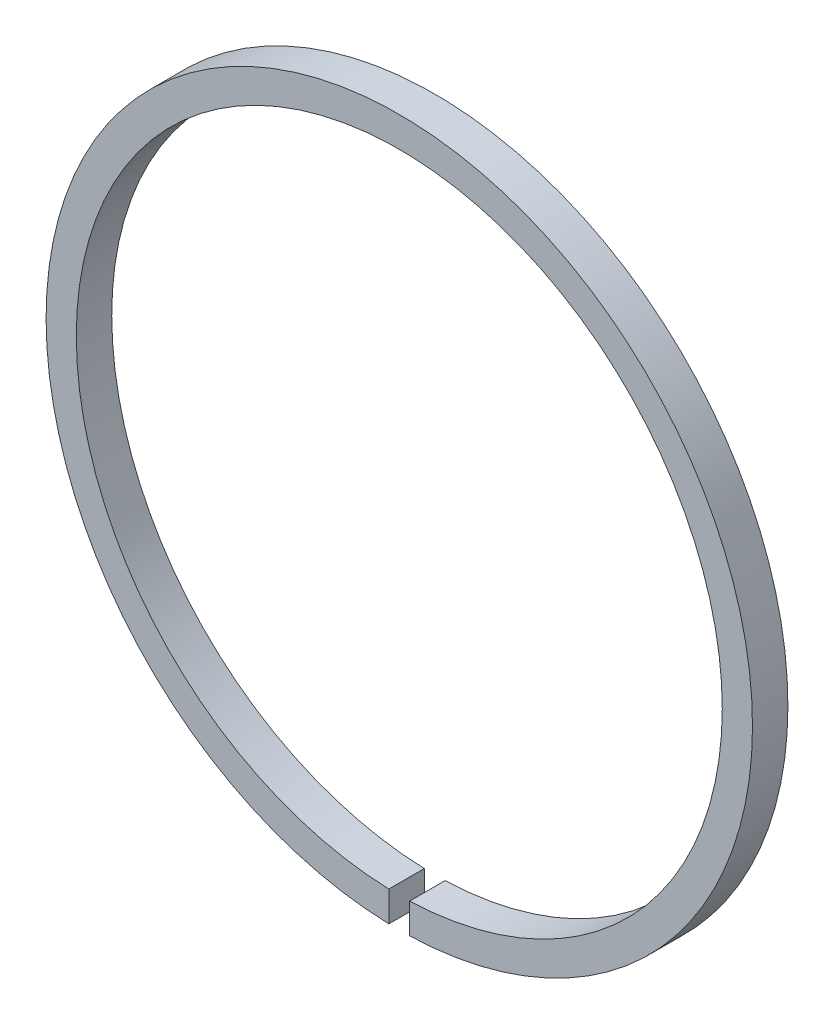
SolidWorks part; units mm, degrees
material "Copper"
ref_plane "Front Plane" through (0, 0, 0) normal (0, 0, 1) x (1, 0, 0)
ref_plane "Top Plane" through (0, 0, 0) normal (0, 1, 0) x (1, 0, 0)
ref_plane "Right Plane" through (0, 0, 0) normal (1, 0, 0) x (0, 0, -1)
sketch "Sketch1" plane through (0, 0, 0) normal (0, 0, 1) x (1, 0, 0)
  circle A0 centre (0, 0) radius 43.053
  circle A1 centre (0, 0) radius 39.37
  dimension "D1" = 86.106
  dimension "D2" = 78.74
extrude "Boss-Extrude1" add sketch "Sketch1" along normal blind 4.318
sketch "Sketch2" plane through (0, 0, 0) normal (0, 0, 1) x (1, 0, 0)
  line L0 (0, 43.053) -> (0, -43.053) construction
  line L2 (-1.27, -39.3495) -> (1.27, -39.3495)
  line L3 (-1.27, -39.3495) -> (-1.27, -44.0993)
  line L4 (-1.27, -44.0993) -> (1.27, -44.0993)
  line L5 (1.27, -39.3495) -> (1.27, -44.0993)
  circle A0 centre (0, 0) radius 43.053 construction
  circle A1 centre (0, 0) radius 39.37 construction
  dimension "D1" = 1.27
  dimension "D2" = 1.27
extrude "Cut-Extrude1" cut sketch "Sketch2" along normal through all
